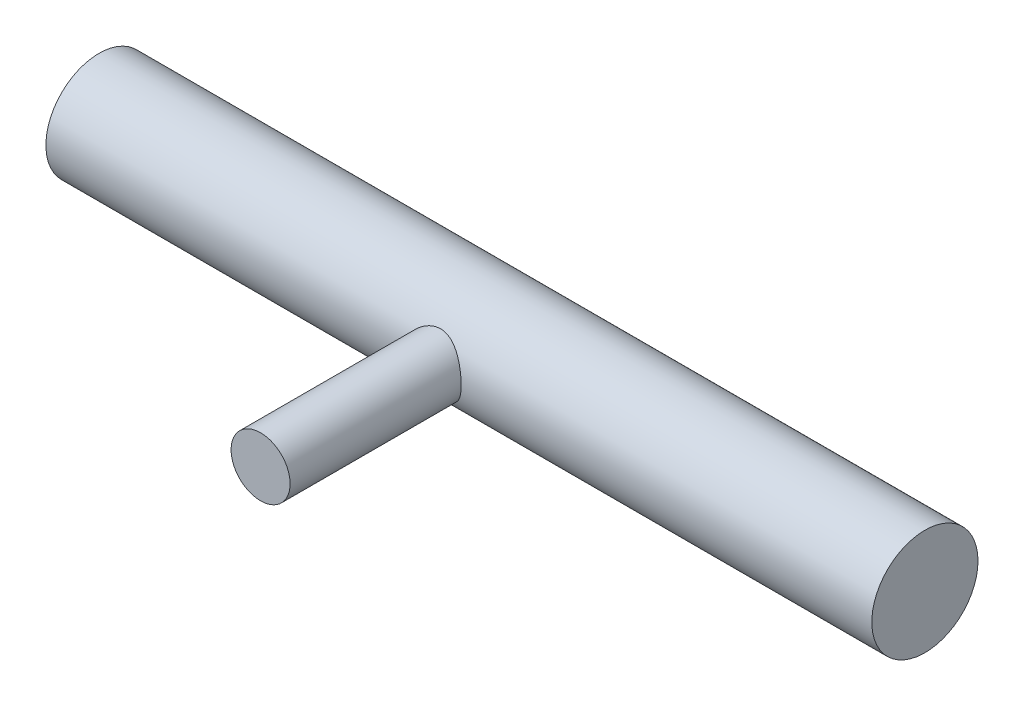
SolidWorks part; units mm, degrees
ref_plane "Front Plane" through (0, 0, 0) normal (0, 0, 1) x (1, 0, 0)
ref_plane "Top Plane" through (0, 0, 0) normal (0, 1, 0) x (1, 0, 0)
ref_plane "Right Plane" through (0, 0, 0) normal (1, 0, 0) x (0, 0, -1)
sketch "Sketch1" plane through (0, 0, 0) normal (1, 0, 0) x (0, 0, -1)
  circle A0 centre (0, 0) radius 4.5
  dimension "D1" = 9
extrude "Boss-Extrude1" add sketch "Sketch1" along normal blind 70
ref_plane "Plane1" through (0, 0, 4) normal (0, 0, 1) x (1, 0, 0)
sketch "Sketch2" plane through (0, 0, 4) normal (0, 0, 1) x (1, 0, 0)
  circle A0 centre (32.6967, 0) radius 2.5
  dimension "D1" = 5
extrude "Boss-Extrude2" add sketch "Sketch2" along normal blind 15 and the other way blind 3
sketch "Sketch4" plane through (0, 0, 0) normal (-1, 0, 0) x (0, 0, 1)
  point P0 (0, 0)
